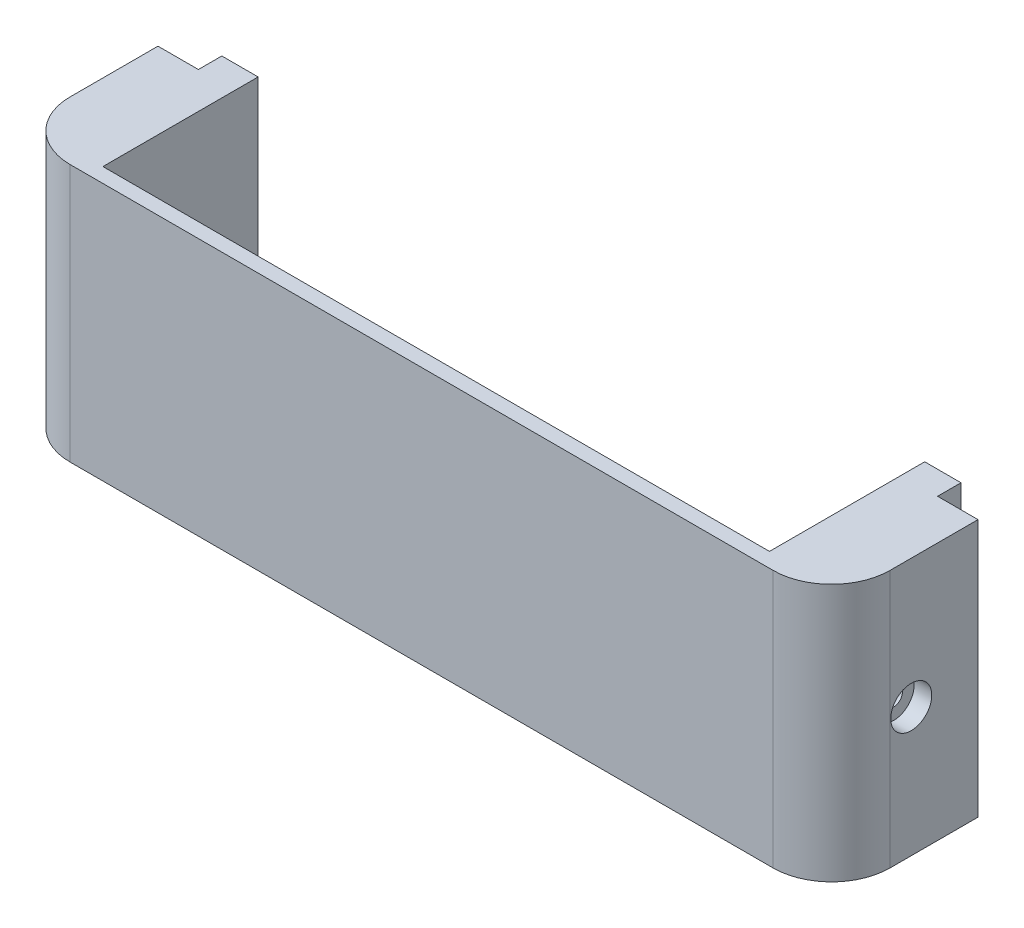
SolidWorks part; units mm, degrees
ref_plane "Front Plane" through (0, 0, 0) normal (0, 0, 1) x (1, 0, 0)
ref_plane "Top Plane" through (0, 0, 0) normal (0, 1, 0) x (1, 0, 0)
ref_plane "Right Plane" through (0, 0, 0) normal (1, 0, 0) x (0, 0, -1)
other "Configuration Table"
sketch "草图1" plane through (0, 0, 0) normal (0, 0, 1) x (1, 0, 0)
  line L0 (-15, 22) -> (-15, -22)
  line L1 (0, 22) -> (15, 22)
  line L2 (0, 22) -> (-15, 22)
  line L3 (15, 22) -> (15, -22)
  line L4 (15, -22) -> (-15, -22)
extrude "凸台-拉伸1" add sketch "草图1" along normal blind 14 contours L0 L4 L3 L1 L2
sketch "草图2" plane through (0, 22, 0) normal (0, 1, 0) x (1, 0, 0)
  line L3 (10, -4) -> (15, -14)
  line L4 (15, -14) -> (-15, -14)
  line L6 (-15, -14) -> (-10, -4)
  line L8 (3.1, -4) -> (3.1, 0)
  line L9 (-15, 0) -> (15, 0) construction
  line L10 (3.1, 0) -> (15, 0)
  line L11 (15, 0) -> (15, -14)
  line L12 (10, -4) -> (3.1, -4)
  line L13 (-3.1, -4) -> (-10, -4)
  line L14 (-15, -14) -> (-15, 0)
  line L15 (-15, 0) -> (-3.1, 0)
  line L16 (-3.1, 0) -> (-3.1, -4)
  line M14 (15, 0) -> (-15, 0)
  line M15 (-15, 0) -> (-15, -14)
  line M17 (15, -14) -> (15, 0)
extrude "切除-拉伸1" cut sketch "草图2" against normal blind 44 contours L16 L6 L13 M14 M15 | L12 L3 L8 M17 M14
sketch "草图3" plane through (0, 0, 0) normal (0, 0, -1) x (-1, 0, 0)
  line L2 (-3.1, 3.1) -> (-3.1, -3.1)
  line L4 (3.1, -22) -> (3.1, 22) construction
  line L5 (3.1, 3.1) -> (-3.1, 3.1)
  line L6 (-3.1, -22) -> (-3.1, 22) construction
  line L9 (-3.1, -3.1) -> (3.1, -3.1)
  line L10 (3.1, -22) -> (3.1, 22) construction
  line L11 (3.1, -3.1) -> (3.1, 3.1)
extrude "切除-拉伸2" cut sketch "草图3" against normal blind 4 contours L2 L9 L11 L5
sketch "草图4" plane through (0, 0, 14) normal (0, 0, 1) x (1, 0, 0)
  circle A0 centre (0, 0) radius 4
extrude "切除-拉伸3" cut sketch "草图4" against normal blind 5
sketch "草图5" plane through (0, 0, 9) normal (0, 0, 1) x (1, 0, 0)
  circle A0 centre (0, 0) radius 2.6
extrude "切除-拉伸4" cut sketch "草图5" against normal blind 5 contours A0
sketch "草图6" plane through (0, 0, 14) normal (0, 0, 1) x (1, 0, 0)
  circle A0 centre (0, 0) radius 4
extrude "凸台-拉伸2" add sketch "草图6" against normal blind 10
sketch "草图7" plane through (0, -22, 0) normal (0, -1, 0) x (-1, 0, 0)
  line L0 (-10, -4) -> (-3.1, -4) construction
  line L1 (3.1, 0) -> (-3.1, 0)
  line L2 (3.1, 0) -> (3.1, -4)
  line L3 (3.1, -4) -> (-3.1, -4)
  line L4 (-3.1, 0) -> (-3.1, -4)
  line L5 (-3.1, -4) -> (-3.1, 0) construction
extrude "凸台-拉伸3" add sketch "草图7" against normal blind 40
sketch "草图8" plane through (0, -22, 0) normal (0, -1, 0) x (1, 0, 0)
  line L0 (-10, 4) -> (-10, 14)
  line L1 (15, 14) -> (-15, 14) construction
  line L2 (-10, 14) -> (-15, 14)
  line L3 (-15, 14) -> (-10, 4)
  line L4 (10, 4) -> (10, 14)
  line L5 (10, 14) -> (15, 14)
  line L6 (15, 14) -> (10, 4)
  line M9 (10, 4) -> (15, 14)
  line M10 (15, 14) -> (-15, 14)
  line M11 (-15, 14) -> (-10, 4)
extrude "切除-拉伸5" cut sketch "草图8" against normal blind 50 contours L0 M11 M10 | L4 M9 M10
sketch "草图9" plane through (0, -22, 0) normal (0, -1, 0) x (1, 0, 0)
  line L0 (-10, 4) -> (-10, 29)
  line L5 (10, 4) -> (-10, 4)
  line L6 (10, 4) -> (10, 29)
  line L7 (-10, 29) -> (10, 29)
extrude "凸台-拉伸4" add sketch "草图9" against normal blind 44 contours L7 L6 L5 L0
sketch "草图10" plane through (0, -22, 0) normal (0, -1, 0) x (1, 0, 0)
  line L0 (-10, 29) -> (-10, 19)
  line L1 (-10, 4) -> (-10, 29) construction
  line L2 (0, 29) -> (-10, 29)
  arc A0 (-10, 19) -> (0, 29) centre (0, 19) cw
extrude "切除-拉伸6" cut sketch "草图10" against normal blind 44
sketch "草图11" plane through (0, -22, 0) normal (0, -1, 0) x (1, 0, 0)
  line L1 (120, 0) -> (123.1, 0)
  line L2 (116.9, 4) -> (110, 4)
  line L3 (123.1, 0) -> (123.1, 4)
  line L4 (123.1, 4) -> (130, 4)
  line L9 (116.9, 4) -> (116.9, 0)
  line L10 (116.9, 0) -> (120, 0)
  line L11 (10, 29) -> (110, 29)
  line L12 (10, 29) -> (10, 26.5)
  line L13 (10, 4) -> (10, 29) construction
  line L14 (10, 26.5) -> (110, 26.5)
  line L15 (110, 26.5) -> (110, 4)
  line L17 (110, 29) -> (120, 29)
  line L18 (130, 19) -> (130, 4)
  arc A0 (130, 19) -> (120, 29) centre (120, 19) ccw
extrude "凸台-拉伸5" add sketch "草图11" against normal blind 44 contours L17 A0 L18 L4 L3 L1 L10 L9 L2 L15 L14 L12 L11
sketch "草图12" plane through (0, 22, 0) normal (0, 1, 0) x (1, 0, 0)
  line L0 (3.1, -4) -> (10, -4)
  line L1 (10, -4) -> (10, -26.5)
  line L2 (10, -26.5) -> (3.1, -26.5)
  line L3 (3.1, -26.5) -> (3.1, -4)
  line L4 (116.9, -4) -> (110, -4)
  line L5 (110, -4) -> (110, -26.5)
  line L6 (110, -26.5) -> (116.9, -26.5)
  line L7 (116.9, -26.5) -> (116.9, -4)
extrude "切除-拉伸7" cut sketch "草图12" against normal blind 50 contours L3 L0 L1 L2 | L7 L4 L5 L6
sketch "草图13" plane through (130, 0, 0) normal (1, 0, 0) x (0, 0, -1)
  line L0 (-4, 0) -> (-15.4, 0)
  line L1 (-4, 22) -> (-4, -22) construction
  circle A0 centre (-15.4, 0) radius 3.5
extrude "切除-拉伸9" cut sketch "草图13" against normal blind 3
sketch "草图14" plane through (-10, 0, 0) normal (-1, 0, 0) x (0, 0, 1)
  line L0 (4, 0) -> (15.4, 0)
  line L1 (4, -22) -> (4, 22) construction
  circle A0 centre (15.4, 0) radius 3.5
extrude "切除-拉伸10" cut sketch "草图14" against normal blind 3 contours A0
sketch "草图15" plane through (-7, 0, 0) normal (-1, 0, 0) x (0, 0, 1)
  circle A0 centre (15.4, 0) radius 1.51
extrude "切除-拉伸11" cut sketch "草图15" against normal blind 200
